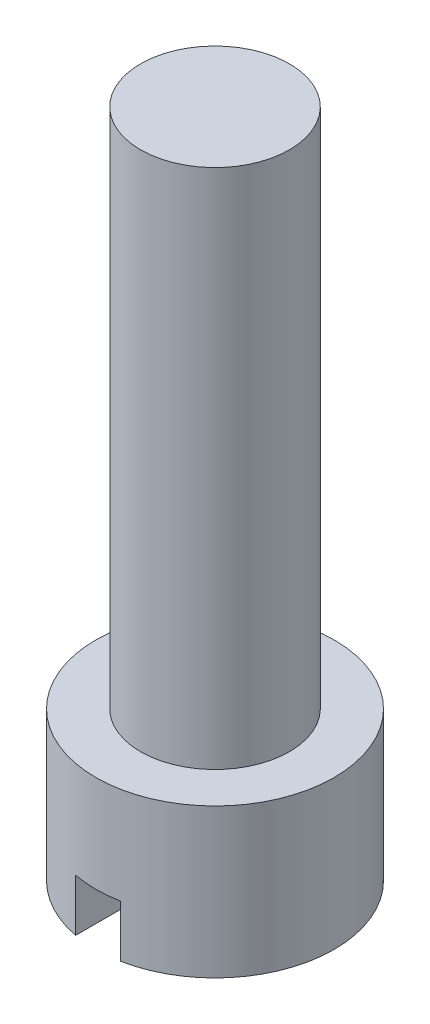
SolidWorks part; units mm, degrees
material "AISI 1020"
ref_plane "Спереди" through (0, 0, 0) normal (0, 0, 1) x (1, 0, 0)
ref_plane "Сверху" through (0, 0, 0) normal (0, 1, 0) x (1, 0, 0)
ref_plane "Справа" through (0, 0, 0) normal (1, 0, 0) x (0, 0, -1)
sketch "Эскиз1" plane through (0, 0, 0) normal (0, 1, 0) x (1, 0, 0)
  circle A0 centre (0, 0) radius 8
  dimension "D1" = 16
extrude "Бобышка-Вытянуть1" add sketch "Эскиз1" along normal blind 10
sketch "Эскиз2" plane through (0, 0, 0) normal (0, 0, 1) x (1, 0, 0)
  line L0 (-8, 0) -> (8, 0) construction
  line L1 (-1.5, 3.5) -> (1.5, 3.5)
  line L2 (-1.5, 3.5) -> (-1.5, 0)
  line L3 (-1.5, 0) -> (1.5, 0)
  line L4 (1.5, 3.5) -> (1.5, 0)
  dimension "D1" = 3
  dimension "D2" = 3.5
extrude "Вырез-Вытянуть1" cut sketch "Эскиз2" against normal mid plane 23.9
sketch "Эскиз3" plane through (0, 10, 0) normal (0, 1, 0) x (1, 0, 0)
  line L0 (-1000, 0) -> (49000, 0) construction
  line L1 (0, -1000) -> (0, 49000) construction
  circle A0 centre (0, 0) radius 5
  dimension "D1" = 10
extrude "Бобышка-Вытянуть2" add sketch "Эскиз3" along normal blind 35
cosmetic thread "Условное изображение резьбы1" parameters "D2"=8.891
